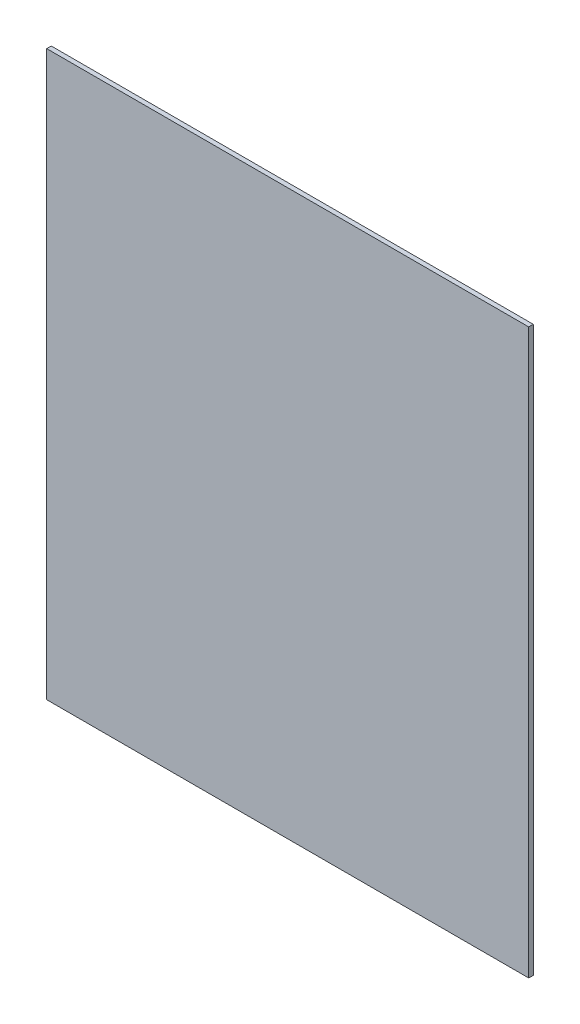
SolidWorks part; units mm, degrees
ref_plane "Plan de face" through (0, 0, 0) normal (0, 0, 1) x (1, 0, 0)
ref_plane "Plan de dessus" through (0, 0, 0) normal (0, 1, 0) x (1, 0, 0)
ref_plane "Plan de droite" through (0, 0, 0) normal (1, 0, 0) x (0, 0, -1)
sketch "Esquisse1" plane through (0, 0, 0) normal (0, 0, 1) x (1, 0, 0)
  line L1 (-265, -310) -> (265, -310)
  line L2 (-265, -310) -> (-265, 310)
  line L3 (-265, 310) -> (265, 310)
  line L4 (265, -310) -> (265, 310)
  line L5 (-265, -310) -> (265, 310) construction
  line L6 (-265, 310) -> (265, -310) construction
  point P0 (0, 0)
  dimension "D1" = 530
  dimension "D2" = 620
extrude "Boss.-Extru.1" add sketch "Esquisse1" along normal blind 5
